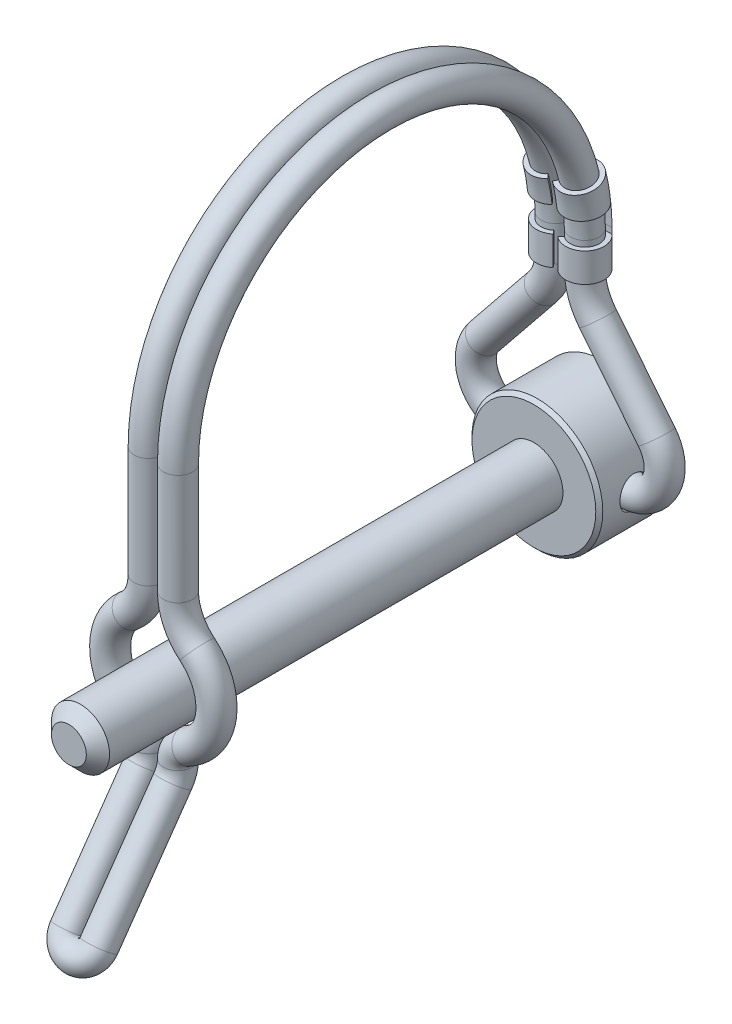
SolidWorks part; units mm, degrees
ref_plane "Front" through (0, 0, 0) normal (0, 0, 1) x (1, 0, 0)
ref_plane "Top" through (0, 0, 0) normal (0, 1, 0) x (1, 0, 0)
ref_plane "Right" through (0, 0, 0) normal (1, 0, 0) x (0, 0, -1)
sketch "Sketch1" plane through (0, 0, 0) normal (1, 0, 0) x (0, 0, -1)
  line L0 (-29.3687, 0) -> (29.3687, 0)
  line L1 (29.3687, 0) -> (29.3687, 6.7627)
  line L2 (28.9877, 7.1437) -> (21.8122, 7.1437)
  line L3 (21.4312, 6.7627) -> (21.4312, 3.175)
  line L4 (21.4312, 3.175) -> (-28.0987, 3.175)
  line L5 (-29.3687, 1.905) -> (-29.3687, 0)
  line L6 (0, 0) -> (0, 3.175) construction
  line L7 (0, 0) -> (0, -3.175) construction
  line L8 (25.4, 7.1437) -> (25.4, 0) construction
  line L9 (25.4, 0) -> (25.4, -7.1438) construction
  line L10 (-28.0987, 3.175) -> (-29.3687, 1.905)
  line L11 (21.8122, 7.1437) -> (21.4312, 6.7627)
  line L12 (29.3687, 6.7627) -> (28.9877, 7.1437)
  point P4 (29.3687, 7.1437)
  point P5 (21.4312, 7.1437)
  point P7 (-29.3687, 3.175)
  dimension "D1" = 6.35
  dimension "D2" = 14.2875
  dimension "D3" = 7.9375
  dimension "D4" = 50.8
revolve "Revolve1" add sketch "Sketch1" angle 360 mid plane about L0
sketch "Sketch2" plane through (0, 0, 0) normal (1, 0, 0) x (0, 0, -1)
  line L0 (21.4313, 0) -> (29.3688, 0) construction
  line L1 (21.4313, 3.175) -> (21.4313, -3.175) construction
  line L2 (29.3688, -6.7627) -> (29.3688, 6.7627) construction
  circle A0 centre (25.4, 0) radius 1.7145
  dimension "D1" = 3.429
extrude "Cut-Extrude1" cut sketch "Sketch2" against normal through all and the other way through all
ref_plane "Plane1" through (1.6002, 0, 0) normal (1, 0, 0) x (0, 0, -1)
ref_plane "Plane2" through (-1.6002, 0, 0) normal (1, 0, 0) x (0, 0, -1)
sketch "Sketch3" plane through (1.6002, 0, 0) normal (1, 0, 0) x (0, 0, -1)
  line L0 (25.4, 0) -> (25.4, 19.05) construction
  line L1 (25.4, 19.05) -> (25.4, 22.225)
  line L3 (-19.05, 22.225) -> (-19.05, 15.875)
  line L4 (23.8125, 19.05) -> (26.9875, 19.05) construction
  line L5 (25.4, 0) -> (-19.05, 0) construction
  line L6 (-19.05, 0) -> (-19.05, 15.875) construction
  line L7 (3.175, 44.45) -> (3.175, 42.8625) construction
  line L8 (3.175, 42.8625) -> (3.175, 3.175) construction
  line L9 (21.4313, 3.175) -> (-28.0987, 3.175) construction
  line L10 (3.175, 44.45) -> (3.175, 46.0375) construction
  line L11 (-17.4625, 15.875) -> (-20.6375, 15.875) construction
  line L12 (-17.4625, 15.875) -> (3.175, 15.875) construction
  arc A2 (25.4, 22.225) -> (-19.05, 22.225) centre (3.175, 22.225) ccw
  dimension "D1" = 19.05
  dimension "D3" = 15.875
  dimension "D4" = 3.175
  dimension "D5" = 39.6875
  dimension "D6" = 3.175
  dimension "D2" = 20.6375
sketch "Sketch4" plane through (-1.6002, 0, 0) normal (1, 0, 0) x (0, 0, -1)
  line L3 (-19.05, 22.225) -> (-19.05, 15.875) construction
  line L4 (25.4, 19.05) -> (25.4, 22.225) construction
  line L6 (-19.05, 22.225) -> (-19.05, 15.875)
  line L7 (25.4, 19.05) -> (25.4, 22.225)
  arc A2 (25.4, 22.225) -> (-19.05, 22.225) centre (3.175, 22.225) ccw construction
  arc A3 (25.4, 22.225) -> (-19.05, 22.225) centre (3.175, 22.225) ccw
ref_plane "Plane3" through (0, 0, -25.4) normal (0, 0, -1) x (-1, 0, 0)
sketch "Sketch5" plane through (0, 0, -25.4) normal (0, 0, -1) x (-1, 0, 0)
  line L0 (-6.35, 0) -> (6.35, 0)
  line L1 (9.4382, 6.4615) -> (3.009, 14.4266)
  line L3 (-9.4382, 6.4615) -> (-3.009, 14.4266)
  line L4 (-1.6002, 0) -> (-1.6002, 19.05) construction
  line L5 (-1.6002, 19.05) -> (-1.6002, 18.415)
  line L6 (1.6002, 19.05) -> (1.6002, 18.415)
  arc A0 (-9.4382, 6.4615) -> (-6.35, 0) centre (-6.35, 3.9688) ccw
  arc A1 (6.35, 0) -> (9.4382, 6.4615) centre (6.35, 3.9688) ccw
  arc A2 (1.6002, 18.415) -> (3.009, 14.4266) centre (7.9502, 18.415) ccw
  arc A3 (-3.009, 14.4266) -> (-1.6002, 18.415) centre (-7.9502, 18.415) ccw
  point P20 (1.6002, 16.172)
  point P23 (-1.6002, 16.172)
  dimension "D1" = 7.9375
  dimension "D2" = 6.35
  dimension "D3" = 0.635
  dimension "D4" = 12.7
ref_plane "Plane4" through (0, 0, 19.05) normal (0, 0, -1) x (-1, 0, 0)
sketch "Sketch6" plane through (0, 0, 19.05) normal (0, 0, -1) x (-1, 0, 0)
  line L0 (0, 0) -> (0, 1.2146) construction
  line L1 (-1.6002, 15.875) -> (-1.6002, 10.16)
  line L2 (-1.6002, 10.16) -> (-1.6002, -5.715) construction
  line L3 (-1.6002, 0) -> (-1.6002, 19.05) construction
  line L5 (-1.7863, -2.6249) -> (-2.6794, -3.9373) construction
  line L6 (-1.6002, 44.45) -> (-1.6002, 46.0375) construction
  arc A0 (-3.7036, 5.6873) -> (-2.6794, -3.9373) centre (0, 1.2146) ccw
  arc A1 (-1.6002, 10.16) -> (-3.7036, 5.6873) centre (-7.4072, 10.16) cw
  arc A2 (-1.6002, -5.715) -> (-2.6794, -3.9373) centre (-3.604, -5.715) ccw
  circle A3 centre (0, 0) radius 3.175 construction
  dimension "D1" = 10.16
  dimension "D2" = 5.715
sketch "Sketch8" plane through (1.6002, 0, 0) normal (1, 0, 0) x (0, 0, -1)
  line L0 (-19.05, -5.715) -> (-22.225, -5.715) construction
  line L1 (-19.6242, -7.5361) -> (-27.6863, -19.05)
  line L2 (-19.05, 10.16) -> (-19.05, -5.715) construction
  line L3 (25.4, 0) -> (-19.05, 0) construction
  arc A0 (-19.6242, -7.5361) -> (-19.05, -5.715) centre (-22.225, -5.715) ccw
  dimension "D1" = 145
  dimension "D2" = 19.05
  dimension "D3" = 3.175
sketch "Sketch9" plane through (0, 0, 19.05) normal (0, 0, -1) x (-1, 0, 0)
  line L0 (0, 0) -> (0, 6.7627) construction
  line L1 (-1.6002, 15.875) -> (-1.6002, 10.16) construction
  line L2 (-1.6002, 15.875) -> (-1.6002, 10.16) construction
  line L3 (1.6002, 15.875) -> (1.6002, 10.16)
  circle A0 centre (0, 0) radius 6.7627 construction
  arc A1 (-3.7036, 5.6873) -> (-1.6002, 10.16) centre (-7.4072, 10.16) ccw construction
  arc A2 (-3.7036, 5.6873) -> (-2.6794, -3.9373) centre (0, 1.2146) ccw construction
  arc A3 (-1.6002, -5.715) -> (-2.6794, -3.9373) centre (-3.604, -5.715) ccw construction
  arc A4 (-3.7036, 5.6873) -> (-1.6002, 10.16) centre (-7.4072, 10.16) ccw construction
  arc A5 (-3.7036, 5.6873) -> (-2.6794, -3.9373) centre (0, 1.2146) ccw construction
  arc A6 (-1.6002, -5.715) -> (-2.6794, -3.9373) centre (-3.604, -5.715) ccw construction
  arc A7 (1.6002, -5.715) -> (2.6794, -3.9373) centre (3.604, -5.715) cw
  arc A8 (3.7036, 5.6873) -> (2.6794, -3.9373) centre (0, 1.2146) cw
  arc A9 (3.7036, 5.6873) -> (1.6002, 10.16) centre (7.4072, 10.16) cw
sketch "Sketch10" plane through (-1.6002, 0, 0) normal (1, 0, 0) x (0, 0, -1)
  line L0 (-19.6242, -7.5361) -> (-27.6863, -19.05) construction
  line L1 (-19.6242, -7.5361) -> (-27.6863, -19.05)
  arc A0 (-19.6242, -7.5361) -> (-19.05, -5.715) centre (-22.225, -5.715) ccw construction
  arc A1 (-19.6242, -7.5361) -> (-19.05, -5.715) centre (-22.225, -5.715) ccw
ref_plane "Plane5" through (0, 6.7411, 9.6272) normal (0, 0.5736, 0.8192) x (1, 0, 0)
sketch "Sketch11" plane through (0, 6.7411, 9.6272) normal (0, 0.5736, 0.8192) x (1, 0, 0)
  line L0 (-1.6002, -31.4851) -> (1.6002, -31.4851) construction
  line L1 (-1.6002, -17.4292) -> (-1.6002, -31.4851) construction
  line L2 (1.6002, -17.4292) -> (1.6002, -31.4851) construction
  line L3 (0, -31.4851) -> (0, -33.0853) construction
  line L4 (0, -33.0853) -> (0, -34.6855) construction
  arc A0 (-1.6002, -31.4851) -> (1.6002, -31.4851) centre (0, -31.4851) ccw
sketch "Sketch7" plane through (0, 0, 0) normal (1, 0, 0) x (0, 0, -1)
  circle A0 centre (25.4, 0) radius 1.5875
  dimension "D1" = 3.175
curve "CompCurve1"
sweep "Sweep1" add profiles "Sketch7" path "CompCurve1"
sketch "Sketch12" plane through (0, 0, 0) normal (1, 0, 0) x (0, 0, -1)
  line L0 (26.9875, 18.415) -> (26.9875, 22.225)
  line L2 (3.175, 22.225) -> (26.2977, 27.915) construction
  arc A0 (26.9875, 22.225) -> (-20.6375, 22.225) centre (3.175, 22.225) ccw construction
  arc A1 (26.9875, 22.225) -> (26.2977, 27.915) centre (3.175, 22.225) ccw
  dimension "D1" = 9.525
ref_plane "Plane6" through (0, 18.415, 0) normal (0, -1, 0) x (-1, 0, 0)
sketch "Sketch13" plane through (0, 18.415, 0) normal (0, -1, 0) x (-1, 0, 0)
  line L0 (1.6002, 26.9875) -> (-1.6002, 26.9875)
  line L1 (1.6002, 27.4955) -> (-1.6002, 27.4955)
  line L2 (0.254, 23.7941) -> (0.5804, 24.1834)
  line L3 (-0.254, 23.7941) -> (-0.5804, 24.1834)
  line L4 (0.254, 23.7941) -> (-0.254, 23.7941) construction
  line L5 (0, 27.4955) -> (0, 26.9875) construction
  line L6 (0, 26.9875) -> (0, 23.7941) construction
  arc A0 (0.5804, 24.1834) -> (1.6002, 26.9875) centre (1.6002, 25.4) ccw
  arc A1 (-1.6002, 26.9875) -> (-0.5804, 24.1834) centre (-1.6002, 25.4) ccw
  arc A3 (-1.6002, 27.4955) -> (-0.254, 23.7941) centre (-1.6002, 25.4) ccw
  arc A4 (0.254, 23.7941) -> (1.6002, 27.4955) centre (1.6002, 25.4) ccw
  dimension "D1" = 0.508
sweep "Sweep2" add profiles "Sketch13" path "Sketch12"
sketch "Sketch14" plane through (0, 0, 0) normal (1, 0, 0) x (0, 0, -1)
  line L0 (26.9875, 21.59) -> (3.175, 21.59)
  line L1 (26.9875, 18.415) -> (26.9875, 22.225) construction
  line L2 (26.8499, 24.7812) -> (3.175, 22.225)
  line L3 (3.175, 22.225) -> (26.2977, 27.915) construction
  line L4 (3.175, 22.225) -> (3.175, 21.59)
  line L5 (26.9875, 21.59) -> (26.9875, 22.225)
  arc A0 (26.9875, 22.225) -> (26.2977, 27.915) centre (3.175, 22.225) ccw construction
  arc A1 (26.9875, 22.225) -> (26.8499, 24.7812) centre (3.175, 22.225) ccw
  dimension "D1" = 3.175
  dimension "D2" = 3.175
extrude "Cut-Extrude2" cut sketch "Sketch14" against normal through all both and the other way through all
equation "\"D1@Plane2\" = \"D1@Plane1\""
equation "\"D6@Sketch3\"=\"D4@Sketch3\""
